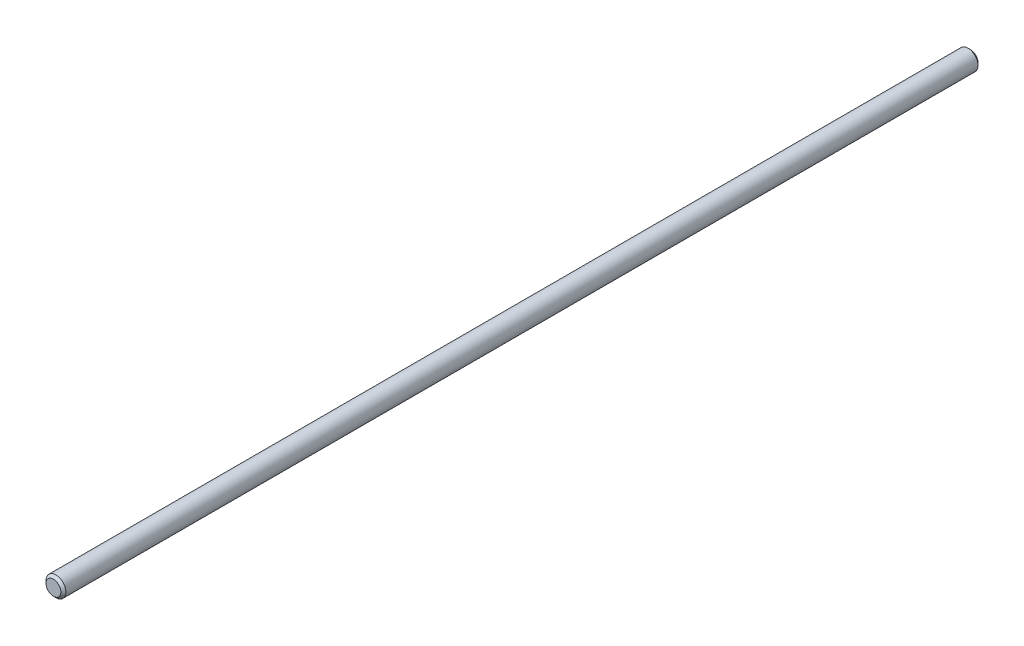
SolidWorks part; units mm, degrees
ref_plane "Piano frontale" through (0, 0, 0) normal (0, 0, 1) x (1, 0, 0)
ref_plane "Piano superiore" through (0, 0, 0) normal (0, 1, 0) x (1, 0, 0)
ref_plane "Piano destro" through (0, 0, 0) normal (1, 0, 0) x (0, 0, -1)
sketch "Schizzo1" plane through (0, 0, 0) normal (0, 0, 1) x (1, 0, 0)
  circle A0 centre (0, 0) radius 4
  dimension "D1" = 8
extrude "Estrusione-Estrusione1" add sketch "Schizzo1" along normal blind 370
chamfer "Smusso1" distance 1 angle 45 2 edges at (4, 0, 370) (4, 0, 0)
